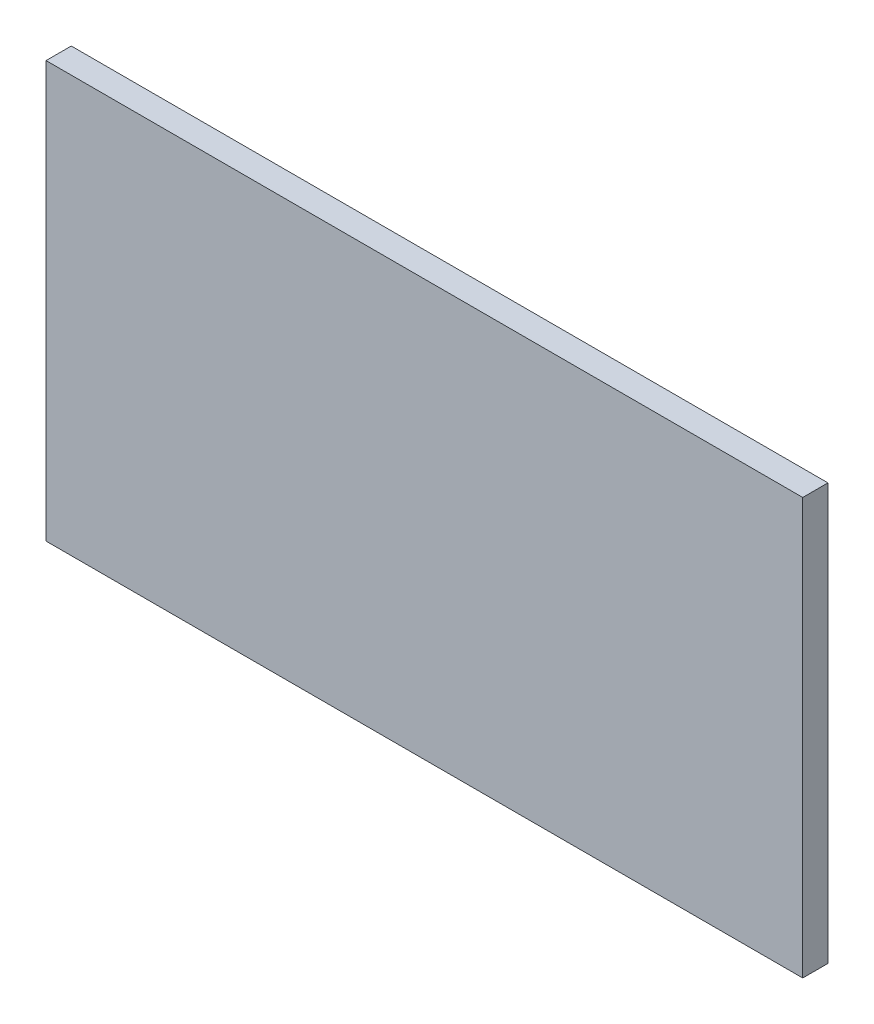
SolidWorks part; units mm, degrees
ref_plane "정면" through (0, 0, 0) normal (0, 0, 1) x (1, 0, 0)
ref_plane "윗면" through (0, 0, 0) normal (0, 1, 0) x (1, 0, 0)
ref_plane "우측면" through (0, 0, 0) normal (1, 0, 0) x (0, 0, -1)
sketch "스케치1" plane through (0, 0, 0) normal (0, 0, 1) x (1, 0, 0)
  line L1 (0, 0) -> (300, 0)
  line L2 (0, 0) -> (0, 165)
  line L3 (0, 165) -> (300, 165)
  line L4 (300, 0) -> (300, 165)
  dimension "D1" = 165
  dimension "D2" = 300
extrude "보스-돌출1" add sketch "스케치1" along normal blind 10
sketch "스케치2" plane through (0, 0, 10) normal (0, 0, 1) x (1, 0, 0)
  line L12 (300, 0) -> (300, 165) construction
  line L13 (0, 62.5) -> (40, 62.5)
  line L14 (0, 62.5) -> (0, 102.5)
  line L15 (0, 102.5) -> (40, 102.5)
  line L24 (40, 62.5) -> (40, 102.5)
  line L25 (300, 102.5) -> (260, 102.5)
  line L26 (300, 102.5) -> (300, 62.5)
  line L27 (300, 62.5) -> (260, 62.5)
  line L28 (260, 102.5) -> (260, 62.5)
  line L29 (300, 165) -> (0, 165) construction
  line L31 (0, 165) -> (0, 0) construction
  point P12 (0, 102.5)
  point P14 (0, 0)
  dimension "D1" = 40
  dimension "D2" = 40
  dimension "D3" = 62.5
  dimension "D4" = 40
  dimension "D5" = 40
  dimension "D6" = 62.5
